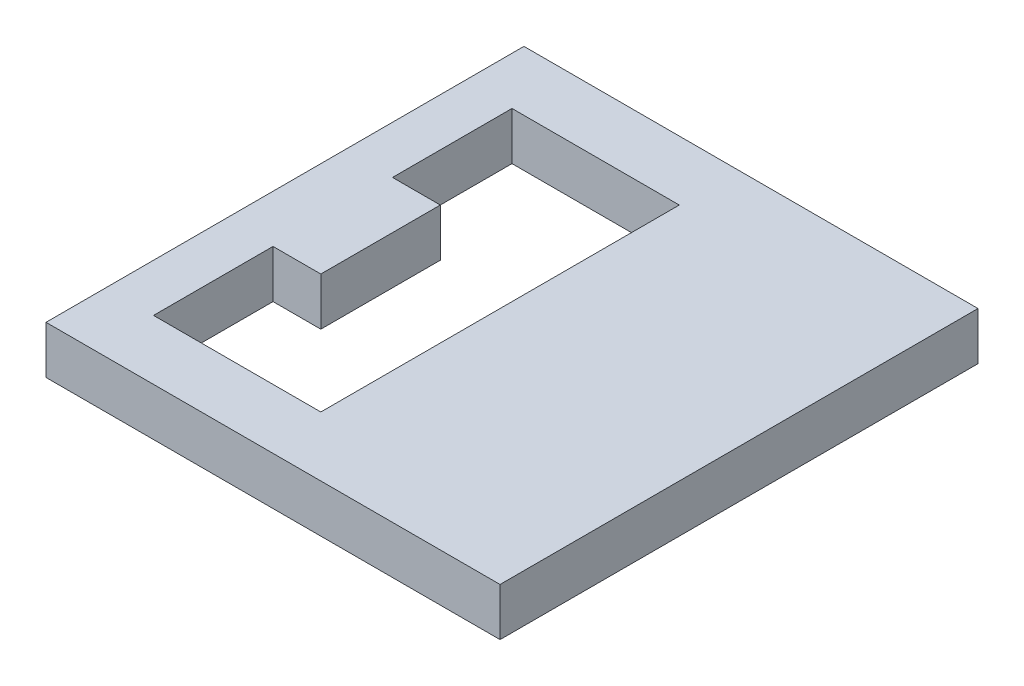
SolidWorks part; units mm, degrees
ref_plane "Front Plane" through (0, 0, 0) normal (0, 0, 1) x (1, 0, 0)
ref_plane "Top Plane" through (0, 0, 0) normal (0, 1, 0) x (1, 0, 0)
ref_plane "Right Plane" through (0, 0, 0) normal (1, 0, 0) x (0, 0, -1)
sketch "Sketch1" plane through (0, 0, 0) normal (0, 1, 0) x (1, 0, 0)
  line L0 (-2, 13.2967) -> (-2, -16.3004) construction
  line L1 (-4, 10) -> (15, 10)
  line L3 (-4, -10) -> (15, -10)
  line L4 (15, 10) -> (15, -10)
  line L5 (-4, 2.6667) -> (15, -10) construction
  line L6 (-4, -2.6667) -> (15, 10) construction
  line L7 (-2, 7.5) -> (-2, 2.5)
  line L8 (-2, 7.5) -> (0, 7.5)
  line L9 (-2, 2.5) -> (0, 2.5)
  line L10 (0, 7.5) -> (0, 2.5)
  line L11 (-2, -2.5) -> (-2, -7.5)
  line L12 (-2, -2.5) -> (0, -2.5)
  line L13 (-2, -7.5) -> (0, -7.5)
  line L14 (0, -2.5) -> (0, -7.5)
  line L15 (-4, 10) -> (-4, -10)
  point P0 (0, 0)
  point P8 (0, 5)
  point P15 (0, -5)
  dimension "D1" = 2
  dimension "D3" = 17
  dimension "D4" = 2
  dimension "D5" = 2
  dimension "D6" = 5
  dimension "D7" = 5
  dimension "D8" = 5
  dimension "D9" = 5
extrude "Boss-Extrude1" add sketch "Sketch1" along normal blind 2
sketch "Sketch2" plane through (0, 2, 0) normal (0, 1, 0) x (1, 0, 0)
  line L0 (0, 7.5) -> (0, -7.5)
  line L1 (0, -7.5) -> (5, -7.5)
  line L2 (5, -7.5) -> (5, 7.5)
  line L3 (5, 7.5) -> (0, 7.5)
  dimension "D1" = 5
extrude "Cut-Extrude1" cut sketch "Sketch2" against normal blind 10
